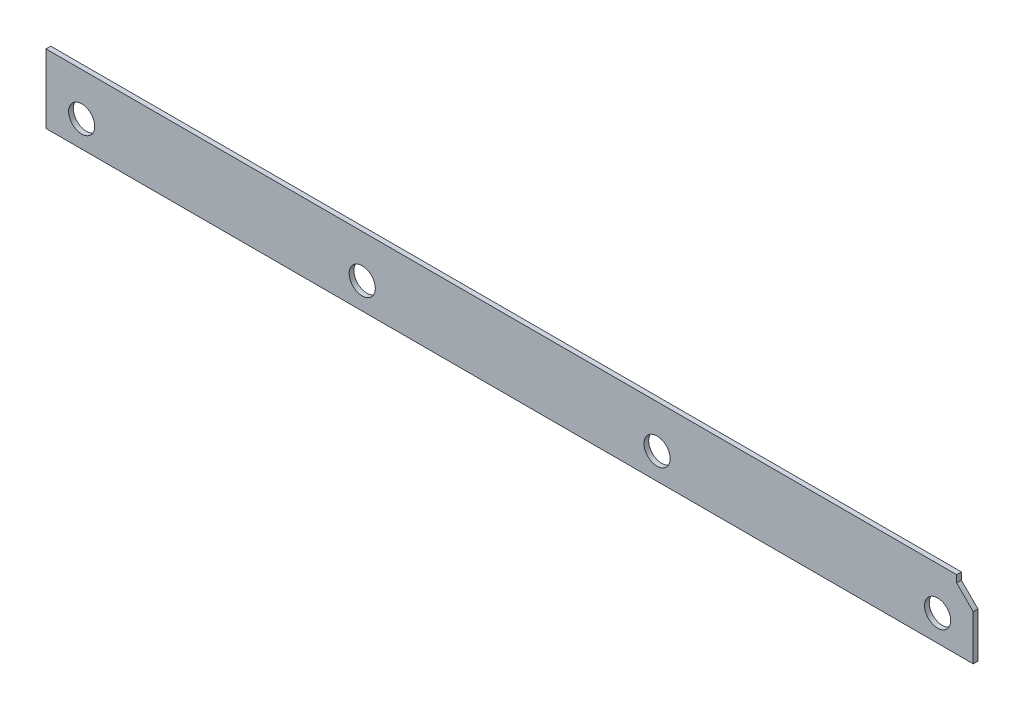
SolidWorks part; units mm, degrees
ref_plane "Front Plane" through (0, 0, 0) normal (0, 0, 1) x (1, 0, 0)
ref_plane "Top Plane" through (0, 0, 0) normal (0, 1, 0) x (1, 0, 0)
ref_plane "Right Plane" through (0, 0, 0) normal (1, 0, 0) x (0, 0, -1)
sketch "Wide flange with original floor bolt centers profile" plane through (0, 0, 0) normal (0, 0, 1) x (1, 0, 0)
  line L0 (-97.5, -14.5) -> (97.5, -14.5)
  line L1 (97.5, -14.5) -> (97.5, -5)
  line L2 (97.5, -5) -> (94, -1.5)
  line L3 (94, -1.5) -> (94, 0)
  line L4 (94, 0) -> (-97.5, 0)
  line L5 (-97.5, 0) -> (-97.5, -14.5)
  circle A0 centre (-90, -9) radius 2.75
  circle A1 centre (-31, -9) radius 2.75
  circle A2 centre (31, -9) radius 2.75
  circle A3 centre (90, -9) radius 2.75
extrude "Wide flange with original floor bolt centers" add sketch "Wide flange with original floor bolt centers profile" along normal blind 1
